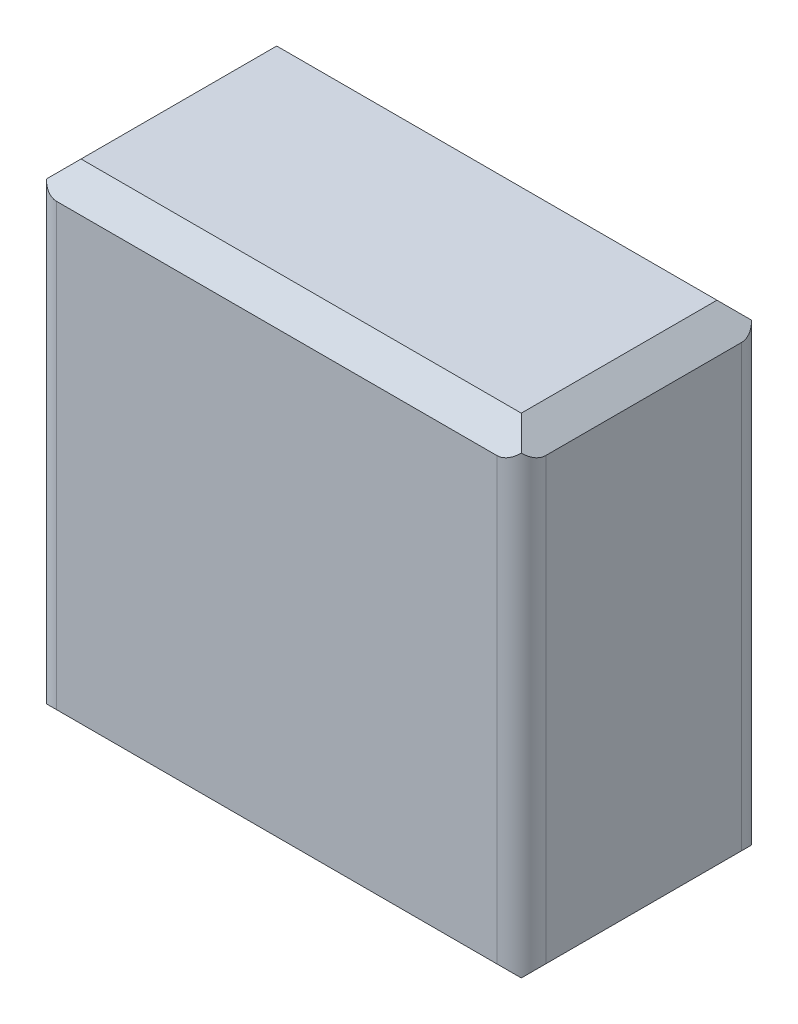
SolidWorks part; units mm, degrees
ref_plane "前视基准面" through (0, 0, 0) normal (0, 0, 1) x (1, 0, 0)
ref_plane "上视基准面" through (0, 0, 0) normal (0, 1, 0) x (1, 0, 0)
ref_plane "右视基准面" through (0, 0, 0) normal (1, 0, 0) x (0, 0, -1)
sketch "草图1" plane through (0, 0, 0) normal (0, 0, 1) x (1, 0, 0)
  line L1 (-28.7361, 40.4282) -> (11.2639, 40.4282)
  line L2 (-28.7361, 40.4282) -> (-28.7361, 0.4282)
  line L3 (-28.7361, 0.4282) -> (11.2639, 0.4282)
  line L4 (11.2639, 40.4282) -> (11.2639, 0.4282)
  dimension "D1" = 40
  dimension "D2" = 40
extrude "凸台-拉伸1" add sketch "草图1" along normal blind 20 contours L2 L3 L4 L1
chamfer "倒角2" distance 2 angle 45 4 edges at (11.2639, 40.4282, 10) (-8.7361, 40.4282, 0) (-28.7361, 40.4282, 10) (-8.7361, 40.4282, 20)
sketch "草图2" plane through (0, 0.4282, 0) normal (0, -1, 0) x (-1, 0, 0)
  line L0 (28.7361, -10) -> (-11.2639, -10) construction
  line L1 (28.7361, -20) -> (28.7361, 0) construction
  line L2 (-11.2639, -20) -> (-11.2639, 0) construction
  line L3 (18.7361, -10) -> (-1.2639, -10) construction
  line L4 (18.7361, -16.4211) -> (-1.2639, -16.4211)
  line L5 (18.7361, -3.5789) -> (-1.2639, -3.5789)
  circle A0 centre (18.7361, -10) radius 5
  arc A1 (18.7361, -16.4211) -> (18.7361, -3.5789) centre (18.7361, -10) ccw
  arc A2 (-1.2639, -3.5789) -> (-1.2639, -16.4211) centre (-1.2639, -10) ccw
  point P8 (8.7361, -10)
  dimension "D2" = 10
  dimension "D1" = 10
  dimension "D3" = 10
extrude "凸台-拉伸3" add sketch "草图2" along normal blind 2 contours A0
sketch "草图4" plane through (0, -1.5718, 0) normal (0, -1, 0) x (1, 0, 0)
  circle A0 centre (-18.7361, 10) radius 2.5
  dimension "D2" = 5
extrude "凸台-拉伸6" add sketch "草图4" along normal blind 3
chamfer "倒角3" distance 2 angle 45 4 edges at (11.2639, 0.4282, 10) (-8.7361, 0.4282, 0) (-28.7361, 0.4282, 10) (-8.7361, 0.4282, 20)
fillet "圆角1" radius 2 4 edges at (11.2639, 20.4282, 0) (11.2639, 20.4282, 20) (-28.7361, 20.4282, 20) (-28.7361, 20.4282, 0)
